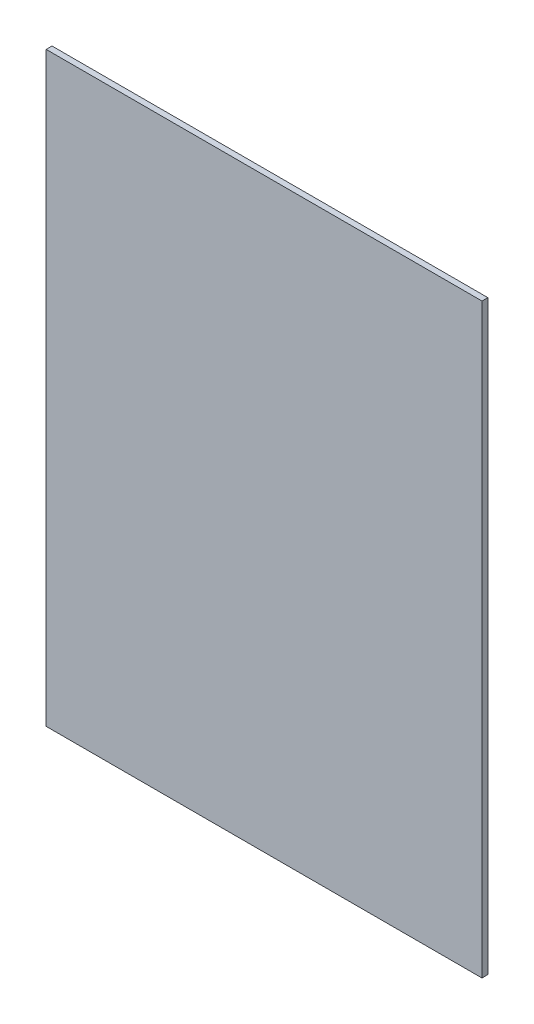
SolidWorks part; units mm, degrees
ref_plane "前视基准面" through (0, 0, 0) normal (0, 0, 1) x (1, 0, 0)
ref_plane "上视基准面" through (0, 0, 0) normal (0, 1, 0) x (1, 0, 0)
ref_plane "右视基准面" through (0, 0, 0) normal (1, 0, 0) x (0, 0, -1)
sketch "草图1" plane through (0, 0, 0) normal (0, 0, 1) x (1, 0, 0)
  line L1 (-111.5, 150) -> (111.5, 150)
  line L2 (-111.5, 150) -> (-111.5, -150)
  line L3 (-111.5, -150) -> (111.5, -150)
  line L4 (111.5, 150) -> (111.5, -150)
  line L5 (-111.5, 150) -> (111.5, -150) construction
  line L6 (-111.5, -150) -> (111.5, 150) construction
  point P0 (0, 0)
  dimension "D1" = 223
  dimension "D2" = 300
extrude "凸台-拉伸1" add sketch "草图1" along normal blind 3
